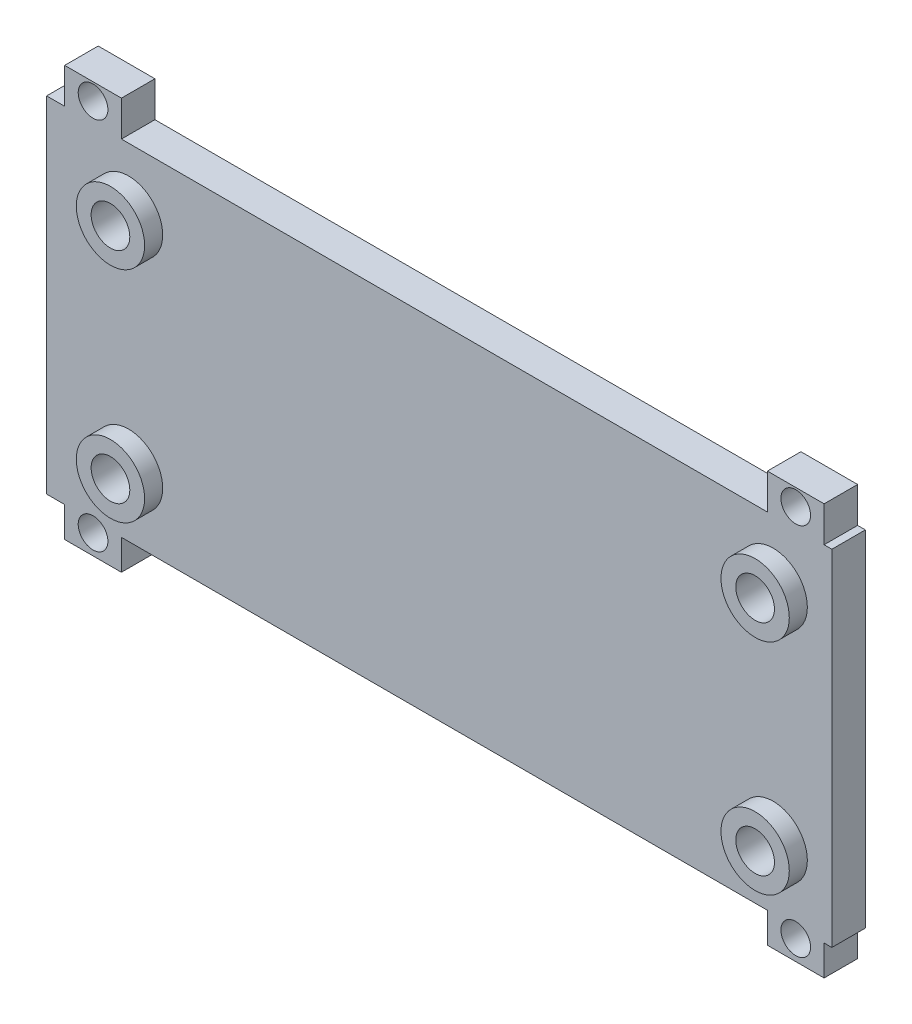
SolidWorks part; units mm, degrees
ref_plane "前视基准面" through (0, 0, 0) normal (0, 0, 1) x (1, 0, 0)
ref_plane "上视基准面" through (0, 0, 0) normal (0, 1, 0) x (1, 0, 0)
ref_plane "右视基准面" through (0, 0, 0) normal (1, 0, 0) x (0, 0, -1)
other "Configuration Table"
sketch "水平悬浮托板及四个可拆安装孔 profile" plane through (0, 0, 0) normal (0, 0, 1) x (1, 0, 0)
  line L0 (-43.1, 4) -> (-41.7, 4)
  line L1 (-41.7, 4) -> (-41.7, 1.65)
  line L2 (-41.7, 1.65) -> (-37.3, 1.65)
  line L3 (-37.3, 1.65) -> (-37.3, 4)
  line L4 (-37.3, 4) -> (12.8, 4)
  line L5 (12.8, 4) -> (12.8, 1.65)
  line L6 (12.8, 1.65) -> (17.2, 1.65)
  line L7 (17.2, 1.65) -> (17.2, 4)
  line L8 (17.2, 4) -> (17.8, 4)
  line L9 (17.8, 4) -> (17.8, 30.75)
  line L10 (17.8, 30.75) -> (17.2, 30.75)
  line L11 (17.2, 30.75) -> (17.2, 33.5)
  line L12 (17.2, 33.5) -> (12.8, 33.5)
  line L13 (12.8, 33.5) -> (12.8, 30.75)
  line L14 (12.8, 30.75) -> (-37.3, 30.75)
  line L15 (-37.3, 30.75) -> (-37.3, 33.5)
  line L16 (-37.3, 33.5) -> (-41.7, 33.5)
  line L17 (-41.7, 33.5) -> (-41.7, 30.75)
  line L18 (-41.7, 30.75) -> (-43.1, 30.75)
  line L19 (-43.1, 30.75) -> (-43.1, 4)
  circle A0 centre (-39.5, 3.2) radius 1.15
  circle A1 centre (15, 3.2) radius 1.15
  circle A2 centre (-39.5, 32.2) radius 1.15
  circle A3 centre (15, 32.2) radius 1.15
  circle A4 centre (-36.75, 8.9) radius 1.5
  circle A5 centre (13.25, 8.9) radius 1.5
  circle A6 centre (-36.75, 25.9) radius 1.5
  circle A7 centre (13.25, 25.9) radius 1.5
extrude "水平悬浮托板及四个可拆安装孔" add sketch "水平悬浮托板及四个可拆安装孔 profile" along normal blind 2.6
sketch "电源板背面焊脚垫空 profile" plane through (0, 0, 0) normal (0, 0, 1) x (1, 0, 0)
  circle A0 centre (-36.75, 8.9) radius 2.65
  circle A1 centre (13.25, 8.9) radius 2.65
  circle A2 centre (-36.75, 25.9) radius 2.65
  circle A3 centre (13.25, 25.9) radius 2.65
  circle A4 centre (-36.75, 8.9) radius 1.5
  circle A5 centre (13.25, 8.9) radius 1.5
  circle A6 centre (-36.75, 25.9) radius 1.5
  circle A7 centre (13.25, 25.9) radius 1.5
extrude "电源板背面焊脚垫空" add sketch "电源板背面焊脚垫空 profile" along normal blind 1.4 from offset 2.6
